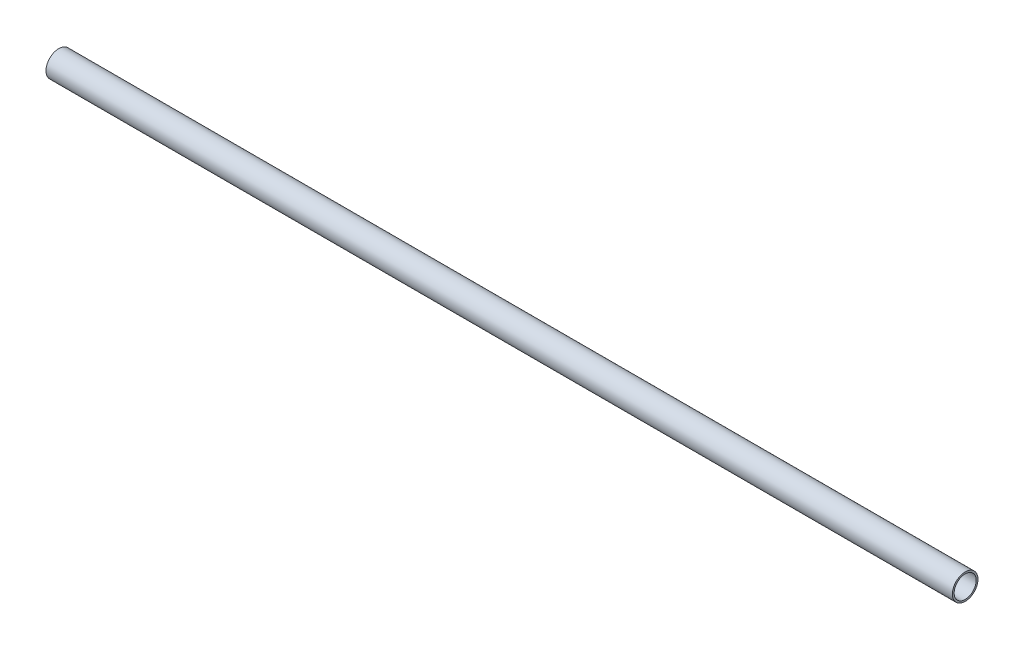
SolidWorks part; units mm, degrees
material "PVC Rigid"
ref_plane "Front Plane" through (0, 0, 0) normal (0, 0, 1) x (1, 0, 0)
ref_plane "Top Plane" through (0, 0, 0) normal (0, 1, 0) x (1, 0, 0)
ref_plane "Right Plane" through (0, 0, 0) normal (1, 0, 0) x (0, 0, -1)
sketch "Sketch1" plane through (0, 0, 0) normal (1, 0, 0) x (0, 0, -1)
  circle A0 centre (0, 0) radius 30.1625
  circle A1 centre (0, 0) radius 25.9969
  dimension "D1" = 60.325
  dimension "D2" = 51.9938
extrude "Boss-Extrude1" add sketch "Sketch1" along normal blind 2133.6
